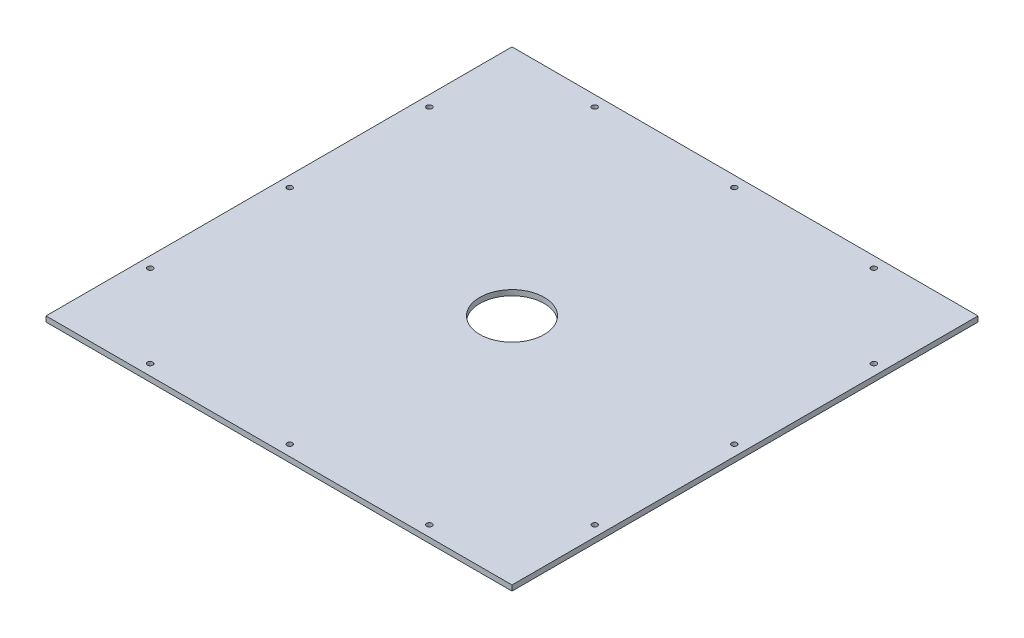
SolidWorks part; units mm, degrees
ref_plane "Front Plane" through (0, 0, 0) normal (0, 0, 1) x (1, 0, 0)
ref_plane "Top Plane" through (0, 0, 0) normal (0, 1, 0) x (1, 0, 0)
ref_plane "Right Plane" through (0, 0, 0) normal (1, 0, 0) x (0, 0, -1)
sketch "Sketch1" plane through (0, 0, 0) normal (0, 1, 0) x (1, 0, 0)
  line L1 (-217, 217) -> (217, 217)
  line L2 (-217, 217) -> (-217, -217)
  line L3 (-217, -217) -> (217, -217)
  line L4 (217, 217) -> (217, -217)
  line L5 (-217, 217) -> (217, -217) construction
  line L6 (-217, -217) -> (217, 217) construction
  point P0 (0, 0)
extrude "Boss-Extrude1" add sketch "Sketch1" along normal blind 5
sketch "Sketch2" plane through (0, 5, 0) normal (0, 1, 0) x (1, 0, 0)
  line L0 (0, 0) -> (0, 76.6055)
  line L1 (0, 0) -> (47.7215, 0)
  line L2 (-217, 217) -> (-207, 217)
  line L3 (217, 217) -> (-217, 217) construction
  line L4 (0, 0) -> (76.6055, 0)
  line L6 (0, 0) -> (0, -47.7215)
  line L7 (0, 0) -> (0, -76.6055)
  line L8 (0, 0) -> (-47.7215, 0)
  line L9 (0, 0) -> (-76.6055, 0)
  line L10 (0, 0) -> (0, 47.7215)
  circle A0 centre (-207, 130) radius 2.5
  circle A1 centre (-207, 0) radius 2.5
  circle A2 centre (-207, -130) radius 2.5
  circle A3 centre (207, -130) radius 2.5
  circle A4 centre (207, 0) radius 2.5
  circle A5 centre (207, 130) radius 2.5
  circle A6 centre (130, 207) radius 2.5
  circle A7 centre (0, 207) radius 2.5
  circle A8 centre (-130, 207) radius 2.5
  circle A9 centre (-130, -207) radius 2.5
  circle A10 centre (0, -207) radius 2.5
  circle A11 centre (130, -207) radius 2.5
  circle A12 centre (207, -130) radius 2.5
  circle A13 centre (207, 0) radius 2.5
  circle A14 centre (207, 130) radius 2.5
  circle A15 centre (-207, 130) radius 2.5
  circle A16 centre (-207, 0) radius 2.5
  circle A17 centre (-207, -130) radius 2.5
  circle A18 centre (-130, -207) radius 2.5
  circle A19 centre (0, -207) radius 2.5
  circle A20 centre (130, -207) radius 2.5
  circle A21 centre (130, 207) radius 2.5
  circle A22 centre (0, 207) radius 2.5
  circle A23 centre (-130, 207) radius 2.5
  point P66 (0, 0)
  dimension "D1" = 4
extrude "Cut-Extrude1" cut sketch "Sketch2" against normal blind 5 contours A2 | A9 | A10 | A11 | A3 | A4 | A5 | A6 | A7 | A8 | A0 | A1
sketch "Sketch3" plane through (0, 5, 0) normal (0, 1, 0) x (1, 0, 0)
  circle A0 centre (0, 0) radius 30
extrude "Cut-Extrude2" cut sketch "Sketch3" against normal blind 5
